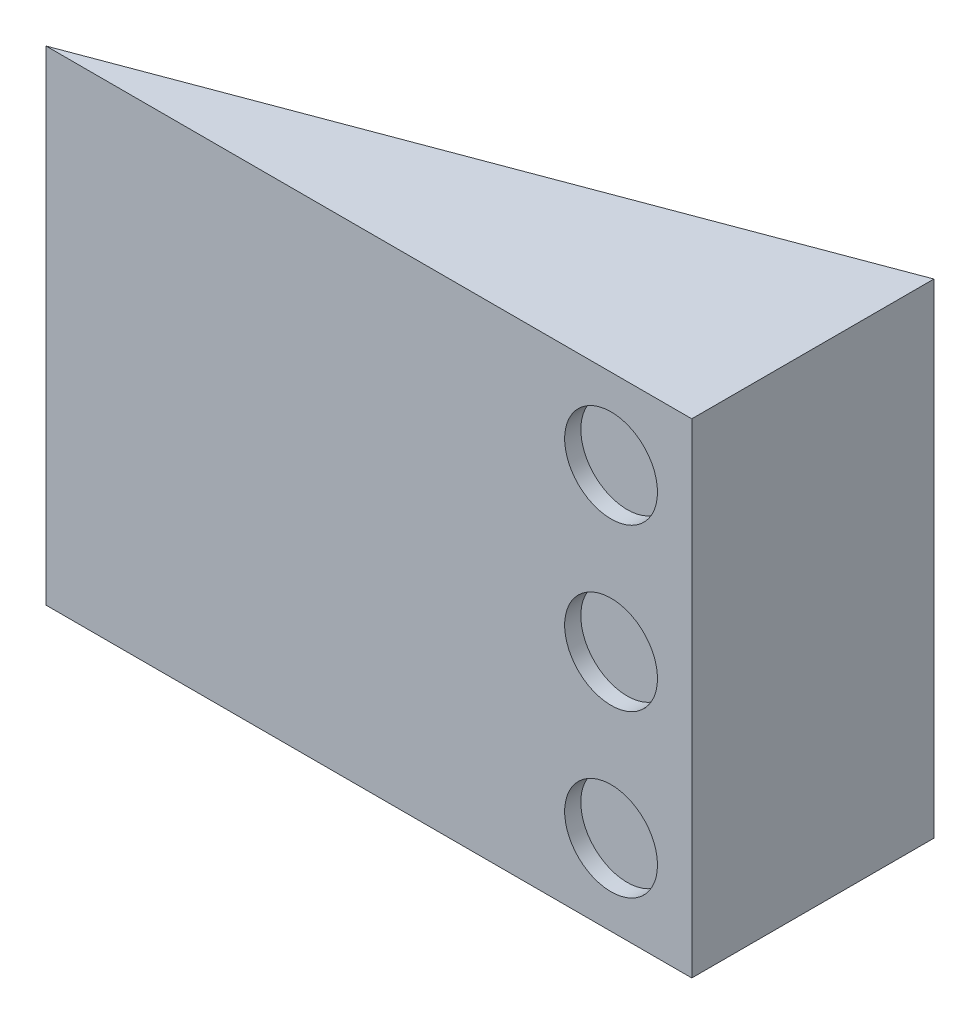
SolidWorks part; units mm, degrees
ref_plane "前视基准面" through (0, 0, 0) normal (0, 0, 1) x (1, 0, 0)
ref_plane "上视基准面" through (0, 0, 0) normal (0, 1, 0) x (1, 0, 0)
ref_plane "右视基准面" through (0, 0, 0) normal (1, 0, 0) x (0, 0, -1)
other "Configuration Table"
sketch "草图1" plane through (0, 0, 0) normal (0, 1, 0) x (1, 0, 0)
  line L0 (0, 0) -> (80, 30)
  line L1 (80, 30) -> (80, 0)
  line L2 (80, 0) -> (0, 0)
  dimension "D1" = 80
  dimension "D2" = 30
extrude "凸台-拉伸1" add sketch "草图1" along normal blind 60
sketch "草图2" plane through (0, 0, 0) normal (0, 0, 1) x (1, 0, 0)
  line L0 (70, 60) -> (70, 50) construction
  line L1 (0, 60) -> (80, 60) construction
  line L2 (70, 50) -> (70, 40) construction
  line L3 (70, 40) -> (70, 30) construction
  line L4 (70, 30) -> (70, 20) construction
  line L5 (70, 20) -> (70, 10) construction
  line L6 (70, 10) -> (70, 0) construction
  line L7 (0, 0) -> (80, 0) construction
  line L9 (80, 60) -> (80, 0) construction
  circle A0 centre (70, 50) radius 5.75
  circle A1 centre (70, 30) radius 5.75
  circle A2 centre (70, 10) radius 5.75
  dimension "D1" = 11.5
  dimension "D2" = 10
extrude "切除-拉伸1" cut sketch "草图2" against normal blind 2
